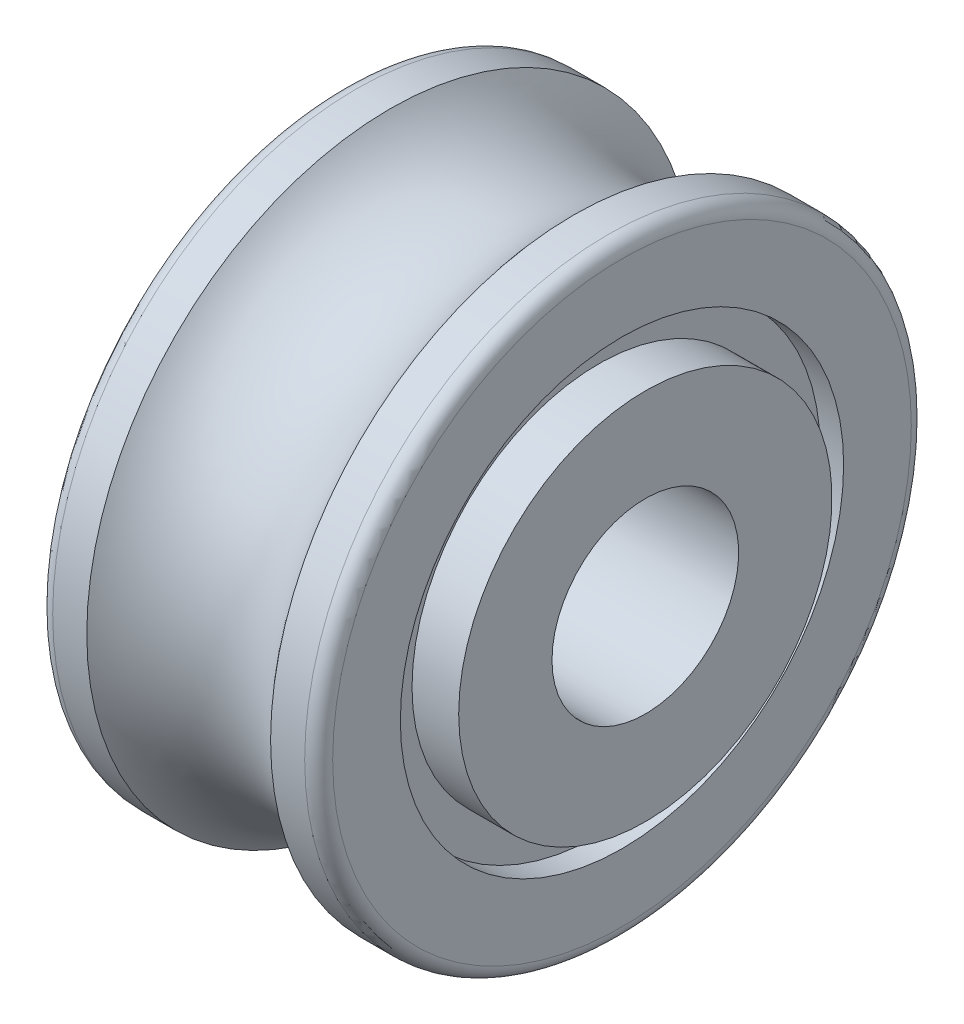
SolidWorks part; units mm, degrees
ref_plane "前视基准面" through (0, 0, 0) normal (0, 0, 1) x (1, 0, 0)
ref_plane "上视基准面" through (0, 0, 0) normal (0, 1, 0) x (1, 0, 0)
ref_plane "右视基准面" through (0, 0, 0) normal (1, 0, 0) x (0, 0, -1)
sketch "草图1" plane through (0, 0, 0) normal (0, 1, 0) x (1, 0, 0)
  line L0 (0, 0) -> (6.7264, 0) construction
  line L1 (-3.5, 2) -> (3.5, 2)
  line L3 (3, 6.5) -> (-3, 6.5)
  line L5 (-3.5, 2) -> (-3.5, 4)
  line L6 (-3.5, 4) -> (-2.5, 4)
  line L7 (-2.5, 4) -> (-2.5, 4.75)
  line L8 (-2.5, 4.75) -> (-3, 4.75)
  line L9 (-3, 4.75) -> (-3, 6.5)
  line L10 (0, 0) -> (0, 7.0446) construction
  line L11 (3, 4.75) -> (3, 6.5)
  line L12 (2.5, 4.75) -> (3, 4.75)
  line L13 (2.5, 4) -> (2.5, 4.75)
  line L14 (3.5, 4) -> (2.5, 4)
  line L15 (3.5, 2) -> (3.5, 4)
  point P19 (0, 6.5)
  point P24 (0, 2)
  dimension "D1" = 4
  dimension "D2" = 13
  dimension "D3" = 7
  dimension "D4" = 6
  dimension "D5" = 8
  dimension "D6" = 9.5
  dimension "D7" = 5
revolve "旋转1" add sketch "草图1" angle 360 about L0
sketch "草图2" plane through (0, 0, 0) normal (0, 1, 0) x (1, 0, 0)
  line L0 (0, 0) -> (-7.983, 0) construction
  circle A0 centre (0, 8.04) radius 2.5
  dimension "D1" = 5
  dimension "D2" = 8.04
revolve "切除-旋转1" cut sketch "草图2" angle 360 about L0
fillet "圆角1" radius 0.3 2 edges at (3, 0, 6.5) (-3, 0, 6.5)
